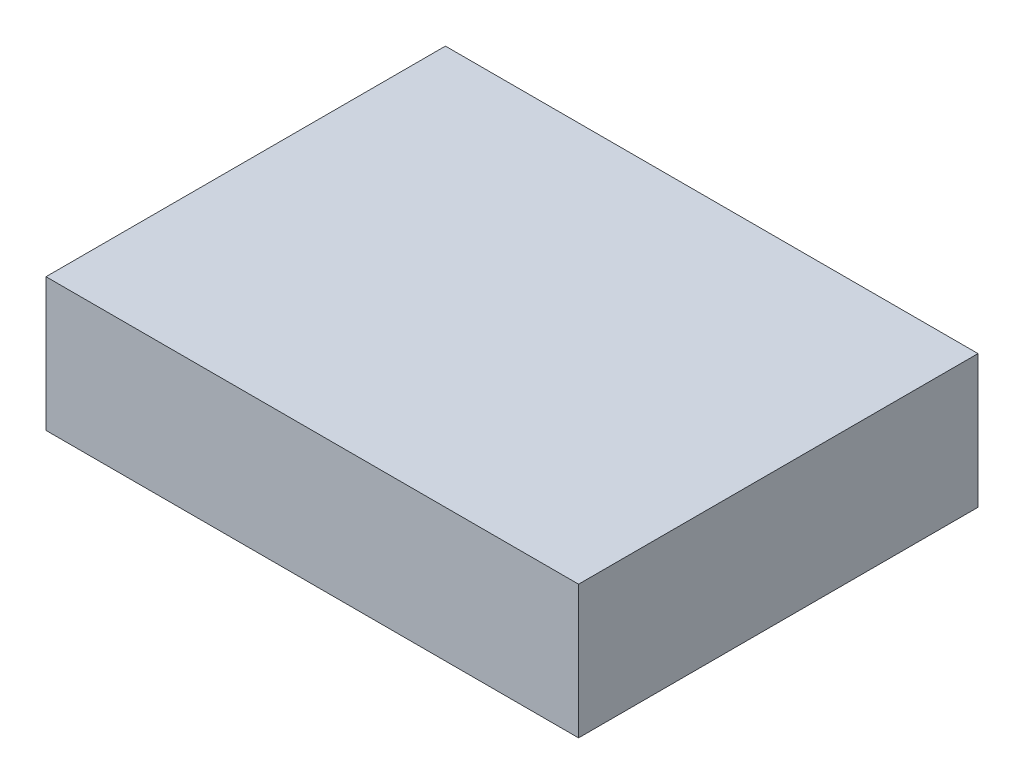
SolidWorks part; units mm, degrees
ref_plane "Front Plane" through (0, 0, 0) normal (0, 0, 1) x (1, 0, 0)
ref_plane "Top Plane" through (0, 0, 0) normal (0, 1, 0) x (1, 0, 0)
ref_plane "Right Plane" through (0, 0, 0) normal (1, 0, 0) x (0, 0, -1)
sketch "Sketch1" plane through (0, 0, 0) normal (0, 1, 0) x (1, 0, 0)
  line L1 (-25.4, -19.05) -> (25.4, -19.05)
  line L2 (-25.4, -19.05) -> (-25.4, 19.05)
  line L3 (-25.4, 19.05) -> (25.4, 19.05)
  line L4 (25.4, -19.05) -> (25.4, 19.05)
  line L5 (-25.4, -19.05) -> (25.4, 19.05) construction
  line L6 (-25.4, 19.05) -> (25.4, -19.05) construction
  point P0 (0, 0)
  dimension "D1" = 50.8
  dimension "D2" = 38.1
extrude "Boss-Extrude1" add sketch "Sketch1" along normal blind 12.7
